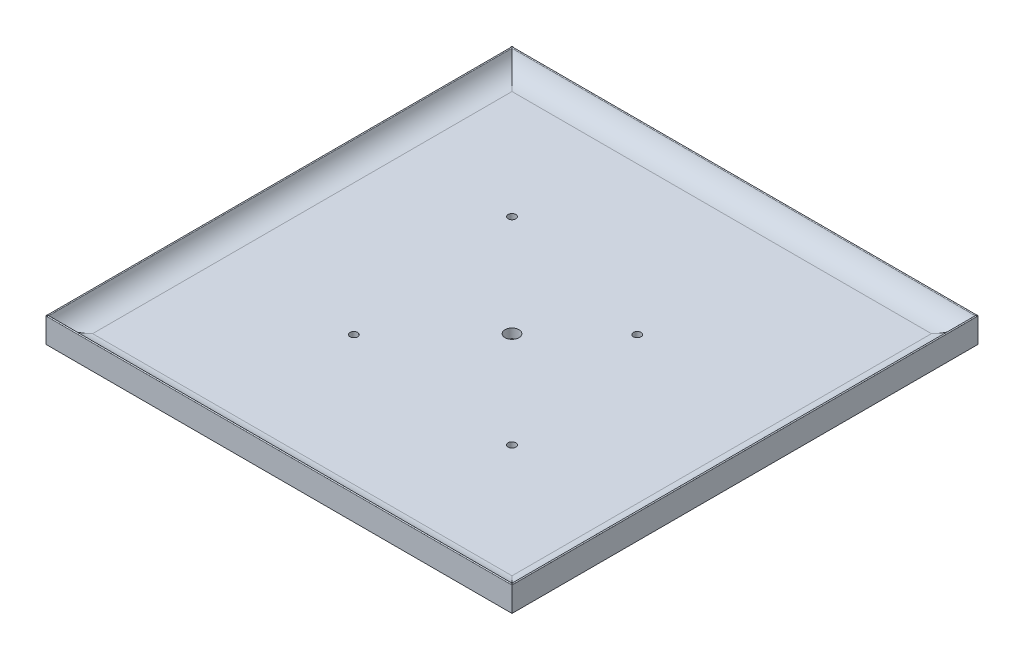
SolidWorks part; units mm, degrees
ref_plane "前视基准面" through (0, 0, 0) normal (0, 0, 1) x (1, 0, 0)
ref_plane "上视基准面" through (0, 0, 0) normal (0, 1, 0) x (1, 0, 0)
ref_plane "右视基准面" through (0, 0, 0) normal (1, 0, 0) x (0, 0, -1)
sketch "草图1" plane through (0, 0, 0) normal (0, 1, 0) x (1, 0, 0)
  line L1 (-100, 100) -> (100, 100)
  line L2 (-100, 100) -> (-100, -100)
  line L3 (-100, -100) -> (100, -100)
  line L4 (100, 100) -> (100, -100)
  line L5 (-100, 100) -> (100, -100) construction
  line L6 (-100, -100) -> (100, 100) construction
  circle A0 centre (0, 0) radius 3
  circle A1 centre (27.2236, 26.5165) radius 1.65
  circle A2 centre (-43.4871, 43.4871) radius 1.65
  circle A3 centre (-33.5876, -34.2947) radius 1.65
  circle A4 centre (41.3657, -41.3657) radius 1.65
  point P0 (0, 0)
  dimension "D3" = 6
  dimension "D4" = 3.3
  dimension "D1" = 200
  dimension "D2" = 200
extrude "凸台-拉伸1" add sketch "草图1" along normal blind 4
sketch "草图3" plane through (0, 0, 0) normal (1, 0, 0) x (0, 0, -1)
  line L0 (-100, 4) -> (-90, 4)
  line L1 (-100, 4) -> (-100, 10.5359)
  line L2 (0, 11.8078) -> (0, 91.7644) construction
  line L3 (-100, 14) -> (0, 14) construction
  line L4 (100, 4) -> (100, 10.5359)
  line L5 (100, 4) -> (90, 4)
  arc A0 (-99.4175, 10.6368) -> (-90, 4) centre (-90, 14) ccw
  arc A1 (-99.4175, 10.6368) -> (-100, 10.5359) centre (-99.7, 10.5359) ccw
  arc A2 (99.4175, 10.6368) -> (100, 10.5359) centre (99.7, 10.5359) cw
  arc A3 (99.4175, 10.6368) -> (90, 4) centre (90, 14) cw
  dimension "D2" = 10
  dimension "D3" = 0.3
  dimension "D1" = 10
extrude "凸台-拉伸3" add sketch "草图3" along normal mid plane 200
sketch "草图5" plane through (0, 0, 0) normal (0, 0, 1) x (1, 0, 0)
  line L0 (-100, 4) -> (-90, 4)
  line L1 (-100, 4) -> (-100, 10.5359)
  line L2 (0, 11.8078) -> (0, 91.7644) construction
  line L3 (-100, 14) -> (0, 14) construction
  line L4 (100, 4) -> (100, 10.5359)
  line L5 (100, 4) -> (90, 4)
  line L6 (-100, 0) -> (100, 0) construction
  line L7 (-100, 10.5359) -> (-100, 0) construction
  arc A0 (-99.4175, 10.6368) -> (-90, 4) centre (-90, 14) ccw
  arc A1 (-99.4175, 10.6368) -> (-100, 10.5359) centre (-99.7, 10.5359) ccw
  arc A2 (99.4175, 10.6368) -> (100, 10.5359) centre (99.7, 10.5359) cw
  arc A3 (99.4175, 10.6368) -> (90, 4) centre (90, 14) cw
  point P17 (0, 0)
  dimension "D2" = 10
  dimension "D3" = 0.3
  dimension "D1" = 10
  dimension "D4" = 4
extrude "凸台-拉伸4" add sketch "草图5" along normal mid plane 200
